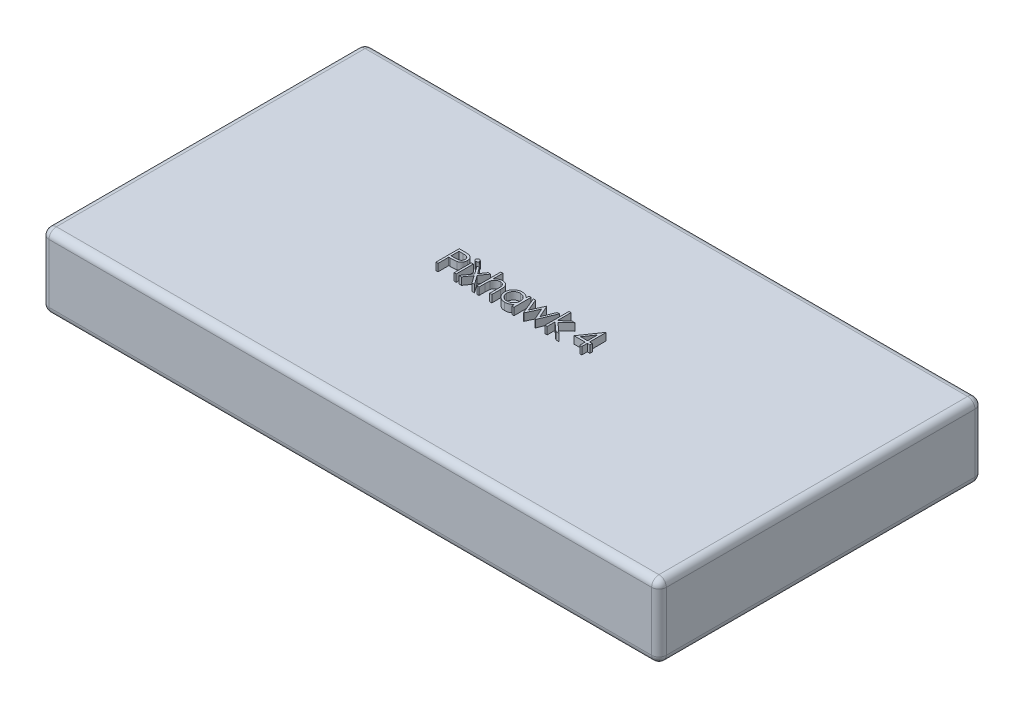
SolidWorks part; units mm, degrees
ref_plane "Front Plane" through (0, 0, 0) normal (0, 0, 1) x (1, 0, 0)
ref_plane "Top Plane" through (0, 0, 0) normal (0, 1, 0) x (1, 0, 0)
ref_plane "Right Plane" through (0, 0, 0) normal (1, 0, 0) x (0, 0, -1)
sketch "Sketch1" plane through (0, 0, 0) normal (0, 1, 0) x (1, 0, 0)
  line L1 (-42, 22) -> (42, 22)
  line L2 (-42, 22) -> (-42, -22)
  line L3 (-42, -22) -> (42, -22)
  line L4 (42, 22) -> (42, -22)
  line L5 (-42, 22) -> (42, -22) construction
  line L6 (-42, -22) -> (42, 22) construction
  point P0 (0, 0)
  dimension "D1" = 84
  dimension "D2" = 44
extrude "Boss-Extrude1" add sketch "Sketch1" along normal blind 10
fillet "Fillet1" radius 1 1 edges at (42, 5, 22)
fillet "Fillet2" radius 1 13 edges at (-42, 5, -22) (0, 10, -22) (42, 5, -22) (0, 0, -22) (-42, 0, 0) (-42, 10, 0) (-42, 5, 22) (-0.5, 10, 22) (41.7071, 10, 21.7071) (41.7071, 0, 21.7071) (-0.5, 0, 22) (42, 0, -0.5) (42, 10, -0.5)
sketch "Sketch2" plane through (0, 10, 0) normal (0, 1, 0) x (1, 0, 0)
  text T0 "Pixhawk 4"
extrude "Boss-Extrude2" add sketch "Sketch2" along normal blind 1
